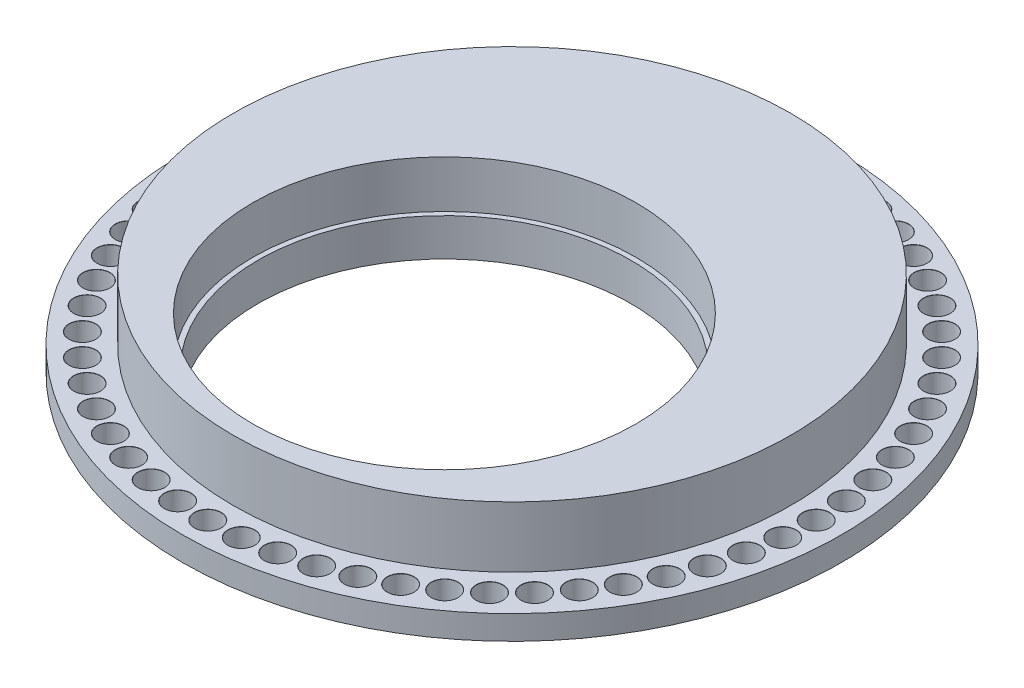
SolidWorks part; units mm, degrees
material "7075-T6 (SN)"
ref_plane "X-Y Datum" through (0, 0, 0) normal (0, 0, 1) x (1, 0, 0)
ref_plane "X-Z Datum" through (0, 0, 0) normal (0, 1, 0) x (1, 0, 0)
ref_plane "Y-Z Datum" through (0, 0, 0) normal (1, 0, 0) x (0, 0, -1)
sketch "Sketch1" plane through (0, 0, 0) normal (0, 1, 0) x (1, 0, 0)
  line L0 (0, 0) -> (0, -12.7) construction
  line L1 (0, -43.0151) -> (0, 43.0151) construction
  line L2 (0, 61.9125) -> (0, 52.3875)
  circle A0 centre (0, -12.7) radius 35.052
  circle A1 centre (0, 0) radius 52.3875 construction
  circle A2 centre (0, 0) radius 57.15 construction
  circle A3 centre (0, 0) radius 61.9125
  point P12 (0, 57.15)
  dimension "D2" = 70.104
  dimension "D3" = 104.775
  dimension "D4" = 123.825
  dimension "D5" = 114.3
  dimension "D1" = 12.7
extrude "Boss-Extrude1" add sketch "Sketch1" along normal blind 4.5212
sketch "Sketch3" plane through (0, 4.5212, 0) normal (0, 1, 0) x (1, 0, 0)
  circle A0 centre (0, 0) radius 52.3875 construction
  circle A1 centre (0, 0) radius 52.3875
extrude "Boss-Extrude2" add sketch "Sketch3" along normal blind 11.43
sketch "Sketch4" plane through (0, 0, 0) normal (0, -1, 0) x (1, 0, 0)
  circle A0 centre (0, 12.7) radius 35.052 construction
  circle A1 centre (0, 12.7) radius 35.052
extrude "Cut-Extrude1" cut sketch "Sketch4" against normal through all
sketch "Sketch9" plane through (0, 15.9512, 0) normal (0, 1, 0) x (1, 0, 0)
  circle A0 centre (0, -12.7) radius 35.052 construction
  circle A1 centre (0, -12.7) radius 35.052 construction
  circle A2 centre (0, -12.7) radius 36
  dimension "D1" = 72
extrude "Cut-Extrude3" cut sketch "Sketch9" against normal blind 8.89
hole_wizard "Ø5.0mm Dowel Hole1" positions "Sketch7" profile "Sketch8" hole size "Ø5.0" standard "ANSI Metric" end condition through all
sketch "Sketch7" plane through (0, 4.5212, 0) normal (0, 1, 0) x (1, 0, 0)
  point P0 (0, 57.15)
sketch "Sketch8" plane through (0, 4.5212, -57.15) normal (1, 0, 0) x (0, 0, 1)
  line L0 (0, 0) -> (0, 4.5212)
  line L1 (0, 4.5212) -> (2.5, 4.5212)
  line L2 (2.5, 4.5212) -> (2.5, 0.025)
  line L3 (2.5, 0.025) -> (2.525, 0)
  line L5 (2.525, 0) -> (0, 0)
  line L6 (-2.5, 0.025) -> (-2.525, 0) construction
  line L11 (0, -6.35) -> (0, 107.95) construction
  dimension "Thru Hole Dia." = 5
  dimension "Thru Hole Depth" = 4.5212
  dimension "Near C'Sink Dia." = 5.05
  dimension "Near C'Sink Angle" = 90
pattern_circular "CirPattern1" count 60 over 360 about axis through (0, 0, 0) along (0, 1, 0) of "Ø5.0mm Dowel Hole1"
ref_plane "Plane1" through (0, 0, 0) normal (-1, 0, 0) x (0, -1, 0)
split line "Split Line1" [suppressed]
ref_point "Point1" [suppressed]
